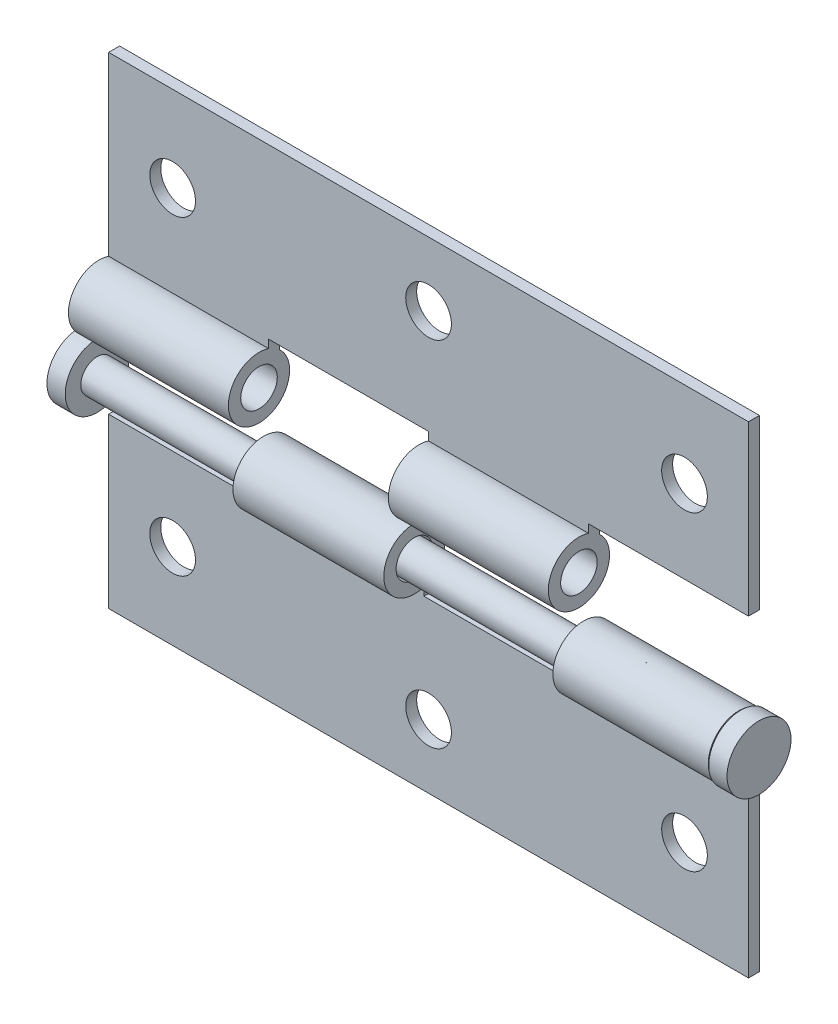
SolidWorks part; units mm, degrees
material "ASTM A36 Steel"
ref_plane "Front Plane" through (0, 0, 0) normal (0, 0, 1) x (1, 0, 0)
ref_plane "Top Plane" through (0, 0, 0) normal (0, 1, 0) x (1, 0, 0)
ref_plane "Right Plane" through (0, 0, 0) normal (1, 0, 0) x (0, 0, -1)
sketch "Sketch1" plane through (0, 0, 0) normal (1, 0, 0) x (0, 0, -1)
  line L0 (-2.25, -3.85) -> (-2.25, -0.5) construction
  line L2 (-1.2, -7.0312) -> (-1.2, -26.35)
  line L3 (-1.2, -26.35) -> (0, -26.35)
  line L4 (0, -6.3319) -> (0, -26.35)
  arc A0 (0, -6.3319) -> (-1.2, -7.0312) centre (-2.25, -3.85) ccw
  circle A1 centre (-2.25, -3.85) radius 2
  dimension "D2" = 6.7
  dimension "D5" = 4
  dimension "D1" = 1.2
  dimension "D3" = 25.85
  dimension "D4" = 2.25
  dimension "D6" = 0.5
extrude "Boss-Extrude1" add sketch "Sketch1" along normal mid plane 70
sketch "Sketch2" plane through (35, 0, 0) normal (1, 0, 0) x (0, 0, -1)
  circle A2 centre (-2.25, -3.85) radius 1.8
  circle A3 centre (-2.25, -3.85) radius 1.8
  dimension "D1" = 0.2
extrude "Boss-Extrude2" add sketch "Sketch2" against normal offset from surface (70.4 mm away) 0.2 from offset 0.2 separate body up to face at (-35, -15.0843, 1.4342) offset beyond the face yes
sketch "Sketch3" plane through (35.2, 0, 0) normal (1, 0, 0) x (0, 0, -1)
  circle A0 centre (-2.25, -3.85) radius 3.5
  circle A1 centre (-2.25, -3.85) radius 1.8 construction
  dimension "D1" = 7
extrude "Boss-Extrude3" add sketch "Sketch3" along normal blind 2
mirror "Mirror1" about plane through (0, 0, 0) normal (1, 0, 0) of "Boss-Extrude3"
mirror "Mirror2" about plane through (0, 0, 0) normal (0, 1, 0) of bodies 103 104
sketch "Sketch4" plane through (0, 0, 0) normal (0, 0, 1) x (1, 0, 0)
  line L0 (35, -0.5) -> (-35, -0.5) construction
  line L1 (-0.5, -0.5) -> (18, -0.5)
  line L2 (-0.5, -0.5) -> (-0.5, -7.9312)
  line L3 (-0.5, -7.9312) -> (18, -7.9312)
  line L4 (18, -0.5) -> (18, -7.9312)
  line L6 (35, 7.0312) -> (35, 26.35) construction
  line L7 (35, 7.9312) -> (17.5, 7.9312)
  line L8 (35, 7.9312) -> (35, 0.5)
  line L9 (35, 0.5) -> (17.5, 0.5)
  line L10 (17.5, 7.9312) -> (17.5, 0.5)
  line L11 (-35, 0.5) -> (35, 0.5) construction
  line L13 (35, -7.0312) -> (-35, -7.0312) construction
  dimension "D2" = 17.5
  dimension "D1" = 0.5
  dimension "D4" = 18.5
  dimension "D3" = 0.9
extrude "Cut-Extrude1" cut sketch "Sketch4" against normal through all both and the other way through all
pattern_linear "LPattern1" count 2 spacing 35 along (-1, 0, 0) of "Cut-Extrude1"
sketch "Sketch5" plane through (0, 0, 1.2) normal (0, 0, 1) x (1, 0, 0)
  line L0 (0, -3.85) -> (0, 3.85) construction
  line L1 (3.85, 0) -> (-3.85, 0) construction
  line L2 (35, -7.0312) -> (35, -26.35) construction
  line L3 (35, -26.35) -> (-35, -26.35) construction
  circle A0 centre (-28, -17) radius 2.5
  circle A1 centre (28, -17) radius 2.5
  circle A2 centre (0, -19.35) radius 2.5
  circle A3 centre (0, 19.35) radius 2.5
  circle A4 centre (28, 17) radius 2.5
  circle A5 centre (-28, 17) radius 2.5
  dimension "D1" = 7
  dimension "D3" = 5
  dimension "D2" = 9.35
  dimension "D4" = 2.35
extrude "Cut-Extrude2" cut sketch "Sketch5" against normal through all
other "Save Bodies1"
equation "\"D1@Boss-Extrude2\" = \"D19@Boss-Extrude2\""
equation "\"D4@Sketch4\" = \"D2@Sketch4\" + \"D1@Sketch4\" * 2"
equation "\"D3@LPattern1\" = \"D2@Sketch4\" * 2"
